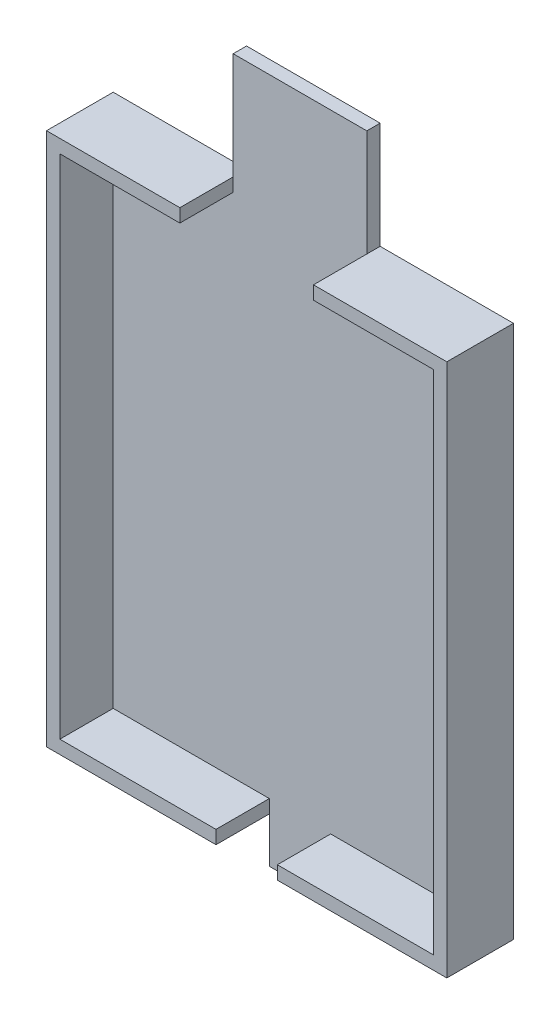
SolidWorks part; units mm, degrees
ref_plane "Front Plane" through (0, 0, 0) normal (1, 0, 0) x (0, 1, 0)
ref_plane "Top Plane" through (0, 0, 0) normal (0, 0, 1) x (0, 1, 0)
ref_plane "Right Plane" through (0, 0, 0) normal (0, 1, 0) x (-1, 0, 0)
sketch "Sketch1" plane through (0, 0, 0) normal (0, 0, 1) x (0, 1, 0)
  line L0 (-65.6505, 9.7136) -> (-65.6505, -13.2864)
  line L1 (-65.6505, -13.2864) -> (-48.6505, -13.2864)
  line L2 (-48.6505, -13.2864) -> (-48.6505, -76.8364)
  line L3 (-48.6505, -76.8364) -> (151.4495, -76.8364)
  line L5 (151.4495, 73.2636) -> (-48.6505, 73.2636)
  line L6 (-48.6505, 73.2636) -> (-48.6505, 9.7136)
  line L7 (-48.6505, 9.7136) -> (-65.6505, 9.7136)
  line L8 (151.4495, 73.2636) -> (151.4495, 23.2636)
  line L9 (151.4495, 23.2636) -> (191.4495, 23.2636)
  line L10 (191.4495, 23.2636) -> (191.4495, -26.8364)
  line L11 (191.4495, -26.8364) -> (151.4495, -26.8364)
  line L12 (151.4495, -26.8364) -> (151.4495, -76.8364)
  dimension "D1" = 150.1
  dimension "D2" = 23
  dimension "D3" = 63.55
  dimension "D4" = 50
  dimension "D5" = 200.1
  dimension "D6" = 40
  dimension "D7" = 50
  dimension "D9" = 200.1
extrude "Boss-Extrude1" add sketch "Sketch1" along normal blind 5
sketch "Sketch7" plane through (0, 0, 5) normal (0, 0, 1) x (1, 0, 0)
  line L0 (-23.2636, 151.4495) -> (-73.2636, 151.4495)
  line L1 (-73.2636, 151.4495) -> (-73.2636, -48.6505)
  line L2 (-73.2636, -48.6505) -> (-9.7136, -48.6505)
  line L3 (-9.7136, -48.6505) -> (-9.7136, -43.6505)
  line L4 (-9.7136, -43.6505) -> (-68.2636, -43.6505)
  line L5 (-68.2636, -43.6505) -> (-68.2636, 146.4495)
  line L6 (-68.2636, 146.4495) -> (-23.2636, 146.4495)
  line L7 (-23.2636, 146.4495) -> (-23.2636, 151.4495)
  dimension "D1" = 5
  dimension "D2" = 5
  dimension "D3" = 5
extrude "Boss-Extrude4" add sketch "Sketch7" along normal blind 20
sketch "Sketch9" plane through (0, 0, 5) normal (0, 0, 1) x (1, 0, 0)
  line L0 (26.8364, 151.4495) -> (76.8364, 151.4495)
  line L1 (76.8364, 151.4495) -> (76.8364, -48.6505)
  line L2 (76.8364, -48.6505) -> (13.2864, -48.6505)
  line L3 (13.2864, -48.6505) -> (13.2864, -43.6505)
  line L4 (13.2864, -43.6505) -> (71.8364, -43.6505)
  line L5 (71.8364, -43.6505) -> (71.8364, 146.4495)
  line L6 (71.8364, 146.4495) -> (26.8364, 146.4495)
  line L7 (26.8364, 146.4495) -> (26.8364, 151.4495)
  dimension "D1" = 5
  dimension "D2" = 5
  dimension "D3" = 5
extrude "Boss-Extrude5" add sketch "Sketch9" along normal blind 20
